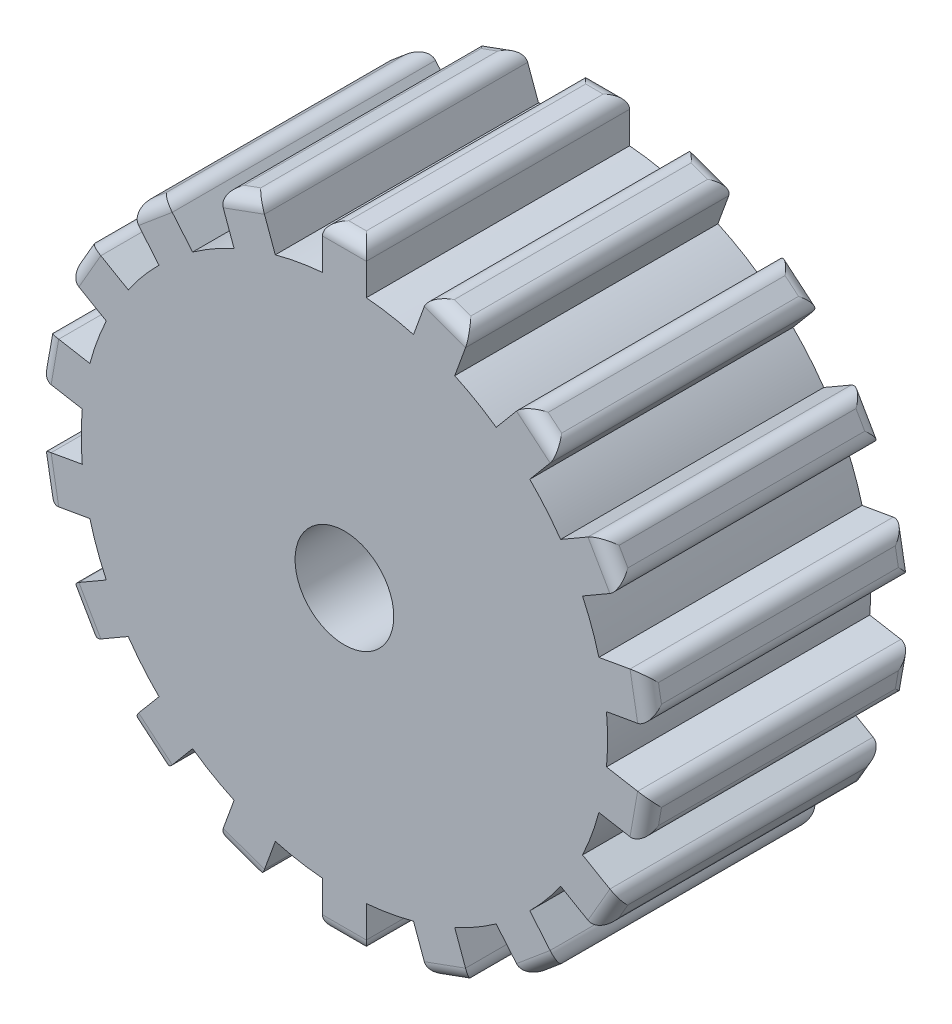
SolidWorks part; units mm, degrees
ref_plane "Front Plane" through (0, 0, 0) normal (0, 0, 1) x (1, 0, 0)
ref_plane "Top Plane" through (0, 0, 0) normal (0, 1, 0) x (1, 0, 0)
ref_plane "Right Plane" through (0, 0, 0) normal (1, 0, 0) x (0, 0, -1)
sketch "Sketch2" plane through (0, 0, 0) normal (0, 0, 1) x (1, 0, 0)
  circle A0 centre (0, 0) radius 60
extrude "Boss-Extrude1" add sketch "Sketch2" along normal blind 60
sketch "Sketch3" plane through (0, 0, 60) normal (0, 0, 1) x (1, 0, 0)
  line L0 (0, 60) -> (0, 70) construction
  line L1 (5, 70) -> (-5, 70)
  line L2 (-5, 70) -> (-5, 59.5215)
  line L3 (-5, 59.5215) -> (5, 59.5215)
  line L4 (5, 59.5215) -> (5, 70)
  circle A0 centre (0, 0) radius 60 construction
  point P9 (0, 70)
extrude "Boss-Extrude2" add sketch "Sketch3" against normal blind 60
fillet "Fillet2" radius 3 4 edges at (-5, 70, 30) (0, 70, 0) (5, 70, 30) (0, 70, 60)
pattern_circular "CirPattern1" count 18 over 360 about axis through (0, 0, 0) along (0, 0, 1) of "Fillet2", "Boss-Extrude2"
sketch "Sketch4" plane through (0, 0, 60) normal (0, 0, 1) x (1, 0, 0)
  circle A0 centre (0, 0) radius 10
extrude "Cut-Extrude1" cut sketch "Sketch4" against normal blind 60
sketch "Sketch5" plane through (0, 0, 0) normal (0, 0, -1) x (-1, 0, 0)
  circle A0 centre (0, 0) radius 11.25
extrude "Cut-Extrude2" cut sketch "Sketch5" against normal up to surface (60 mm away) up to face at (10, 0, 60)
scale "Scale1" bodies to scale 105 scale about centroid uniform scaling yes scale factor 0.2
